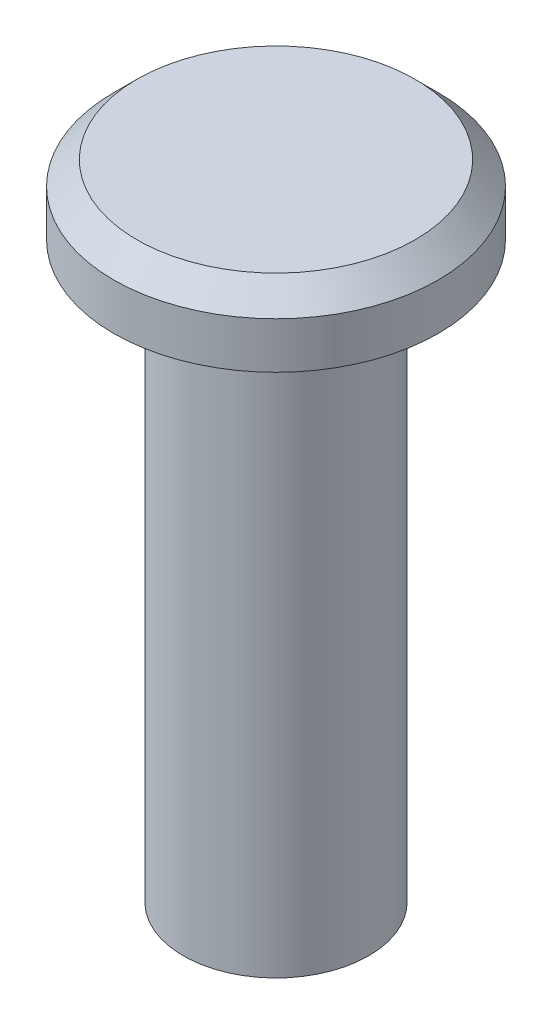
SolidWorks part; units mm, degrees
ref_plane "Front Plane" through (0, 0, 0) normal (0, 0, 1) x (1, 0, 0)
ref_plane "Top Plane" through (0, 0, 0) normal (0, 1, 0) x (1, 0, 0)
ref_plane "Right Plane" through (0, 0, 0) normal (1, 0, 0) x (0, 0, -1)
sketch "Sketch1" plane through (0, 0, 0) normal (0, 0, 1) x (1, 0, 0)
  line L0 (0, 0) -> (4, 0)
  line L1 (4, 0) -> (4, 24.75)
  line L2 (4, 24.75) -> (7, 24.75)
  line L3 (7, 24.75) -> (7, 26.75)
  line L4 (6, 27.75) -> (0, 27.75)
  line L5 (0, 27.75) -> (0, 0)
  line L6 (0, 33.605) -> (0, -11.1185) construction
  line L7 (7, 26.75) -> (6, 27.75)
  point P6 (7, 27.75)
  dimension "D1" = 8
  dimension "D2" = 24.75
  dimension "D3" = 3
  dimension "D4" = 14
revolve "Revolve1" add sketch "Sketch1" angle 360 about L6
cosmetic thread "Cosmetic Thread2" parameters "D1"=3, "D2"=6.561
